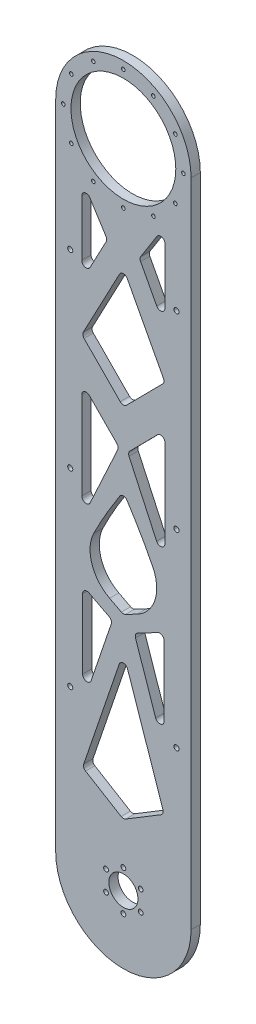
SolidWorks part; units mm, degrees
material "1060 Alloy"
ref_plane "Front Plane" through (0, 0, 0) normal (0, 0, 1) x (1, 0, 0)
ref_plane "Top Plane" through (0, 0, 0) normal (0, 1, 0) x (1, 0, 0)
ref_plane "Right Plane" through (0, 0, 0) normal (1, 0, 0) x (0, 0, -1)
sketch "Sketch2" plane through (0, 0, 0) normal (0, 0, 1) x (1, 0, 0)
  line L0 (0, 0) -> (0, 500) construction
  line L1 (-46.5, 0) -> (-46.5, 500)
  line L2 (46.5, 0) -> (46.5, 500)
  arc A0 (-46.5, 0) -> (46.5, 0) centre (0, 0) ccw
  arc A1 (46.5, 500) -> (-46.5, 500) centre (0, 500) ccw
  circle A2 centre (0, 500) radius 37.25 construction
  circle A3 centre (0, 0) radius 10
  circle A4 centre (0, 13.75) radius 1.65
  circle A5 centre (0, 0) radius 13.75 construction
  circle A6 centre (11.9078, 6.875) radius 1.65
  circle A7 centre (11.9078, -6.875) radius 1.65
  circle A8 centre (0, -13.75) radius 1.65
  circle A9 centre (-11.9078, -6.875) radius 1.65
  circle A10 centre (-11.9078, 6.875) radius 1.65
  point P3 (0, 250)
  point P27 (0, 0)
  dimension "D2" = 74.5
  dimension "D4" = 20
  dimension "D5" = 3.3
  dimension "D6" = 27.5
  dimension "D3" = 46.5
  dimension "D1" = 500
  dimension "D7" = 6
extrude "Boss-Extrude1" add sketch "Sketch2" along normal blind 6.35
sketch "Sketch4" plane through (0, 0, 6.35) normal (0, 0, 1) x (1, 0, 0)
  line L0 (0, 500) -> (0, 999.1647) construction
  line L29 (46.5, 500) -> (-46.5, 500) construction
  line L31 (28.0053, 59.376) -> (0, 42.4117)
  line L32 (0, 141.6934) -> (28.0053, 59.376)
  line L33 (-28.0053, 59.376) -> (0, 141.6934)
  line L34 (0, 42.4117) -> (-28.0053, 59.376)
  line L35 (-7.5, 156.9059) -> (-28.0053, 96.6336)
  line L36 (-28.0053, 167.5829) -> (-7.5, 156.9059)
  line L37 (-28.0053, 96.6336) -> (-28.0053, 167.5829)
  line L38 (28.0053, 167.5829) -> (7.5, 156.9059)
  line L39 (28.0053, 96.6336) -> (28.0053, 167.5829)
  line L40 (7.5, 156.9059) -> (28.0053, 96.6336)
  line L41 (0, 164.2751) -> (28.5505, 179.1412)
  line L42 (0, 164.2751) -> (-28.5505, 179.1412)
  line L43 (28.5505, 259.5868) -> (3, 314.9383)
  line L44 (28.5505, 340.7931) -> (28.5505, 259.5868)
  line L45 (3, 314.9383) -> (28.5505, 340.7931)
  line L46 (-3, 314.9383) -> (-28.5505, 340.7931)
  line L47 (-28.5505, 259.5868) -> (-3, 314.9383)
  line L48 (-28.5505, 340.7931) -> (-28.5505, 259.5868)
  line L49 (0, 423.1428) -> (-28.5505, 369.2462)
  line L50 (-28.5505, 369.2462) -> (0, 340.3557)
  line L51 (0, 340.3557) -> (28.5505, 369.2462)
  line L52 (0, 423.1428) -> (28.5505, 369.2462)
  line L53 (-28.5505, 462.0952) -> (-28.5505, 401.2902)
  line L54 (-11, 434.4215) -> (-28.5505, 462.0952)
  line L55 (-28.5505, 401.2902) -> (-11, 434.4215)
  line L56 (28.5505, 401.2902) -> (11, 434.4215)
  line L57 (28.5505, 462.0952) -> (28.5505, 401.2902)
  line L58 (11, 434.4215) -> (28.5505, 462.0952)
  arc A0 (46.5, 500) -> (-46.5, 500) centre (0, 500) ccw construction
  arc A1 (46.5, 500) -> (-46.5, 500) centre (0, 500) ccw construction
  spline S2 degree 3 poles (28.5505, 179.1412) (45.3203, 216.9857) (19.4301, 259.7903) (0, 290.0258) knots 0 0 0 0 1 1 1 1
  spline S3 degree 3 poles (-28.5505, 179.1412) (-45.3203, 216.9857) (-19.4301, 259.7903) (0, 290.0258) knots 0 0 0 0 1 1 1 1
extrude "Cut-Extrude1" cut sketch "Sketch4" against normal blind 10
fillet "Fillet3" radius 3 30 edges at (-11, 434.4215, 3.175) (-28.5505, 401.2902, 3.175) (28.5505, 401.2902, 3.175) (11, 434.4215, 3.175) (28.5505, 462.0952, 3.175) (-28.5505, 462.0952, 3.175) (0, 423.1428, 3.175) (-28.5505, 369.2462, 3.175) (28.5505, 369.2462, 3.175) (0, 340.3557, 3.175) (28.5505, 340.7931, 3.175) (-28.5505, 340.7931, 3.175) (-3, 314.9383, 3.175) (3, 314.9383, 3.175) (28.5505, 259.5868, 3.175) (-28.5505, 259.5868, 3.175) (28.5505, 179.1412, 3.175) (0, 290.0258, 3.175) (-28.5505, 179.1412, 3.175) (0, 164.2751, 3.175) (-28.0053, 96.6336, 3.175) (28.0053, 96.6336, 3.175) (7.5, 156.9059, 3.175) (-28.0053, 167.5829, 3.175) (28.0053, 167.5829, 3.175) (0, 141.6934, 3.175) (28.0053, 59.376, 3.175) (-28.0053, 59.376, 3.175) (0, 42.4117, 3.175) (-7.5, 156.9059, 3.175)
sketch "Sketch5" plane through (0, 0, 6.35) normal (0, 0, 1) x (1, 0, 0)
  line L0 (0, -46.5) -> (108.8395, -46.5) construction
  line L1 (46.5, 100) -> (-46.5, 100) construction
  line L2 (46.5, 0) -> (46.5, 500) construction
  line L3 (-46.5, 500) -> (-46.5, 0) construction
  line L4 (-46.5, 106.35) -> (46.5, 106.35) construction
  line L5 (36.5, 106.35) -> (36.5, 100) construction
  line L6 (0, 106.35) -> (0, 100) construction
  line L7 (-46.5, 256.35) -> (46.5, 256.35) construction
  line L8 (-46.5, 181.35) -> (46.5, 181.35) construction
  line L9 (-46.5, 337.7) -> (46.5, 337.7) construction
  arc A1 (-46.5, 0) -> (46.5, 0) centre (0, 0) ccw construction
  circle A2 centre (36.5, 103.175) radius 1.75
  circle A3 centre (-36.5, 103.175) radius 1.75
  circle A4 centre (36.5, 259.525) radius 1.75
  circle A5 centre (-36.5, 259.525) radius 1.75
  circle A6 centre (36.5, 415.875) radius 1.75
  circle A7 centre (-36.5, 415.875) radius 1.75
  point P18 (36.5, 103.175)
  dimension "D2" = 3.5
  dimension "D1" = 146.5
  dimension "D3" = 10
  dimension "D4" = 6.35
  dimension "D5" = 150
  dimension "D6" = 81.35
  dimension "D7" = 81.35
extrude "Cut-Extrude2" cut sketch "Sketch5" against normal through all
sketch "Sketch6" plane through (0, 0, 6.35) normal (0, 0, 1) x (1, 0, 0)
  circle A0 centre (0, 500) radius 26.5
  arc A1 (46.5, 500) -> (-46.5, 500) centre (0, 500) ccw construction
  arc A2 (46.5, 500) -> (-46.5, 500) centre (0, 500) ccw construction
  dimension "D1" = 20
extrude "Cut-Extrude3" cut sketch "Sketch6" against normal blind 10
sketch "Sketch7" plane through (0, 0, 6.35) normal (0, 0, 1) x (1, 0, 0)
  line L1 (40.0163, 523.6842) -> (44.1104, 529.9682) construction
  line L2 (23.6842, 540.0163) -> (29.9682, 544.1104) construction
  line L3 (44.1104, 529.9682) -> (29.9682, 544.1104)
  line L4 (0, 500) -> (37.0393, 537.0393) construction
  line L5 (0, 500) -> (0, 546.5) construction
  arc A0 (46.5, 500) -> (-46.5, 500) centre (0, 500) ccw construction
  arc A1 (29.9682, 544.1104) -> (16.4747, 543.4837) centre (22.4977, 559.381) cw
  arc A2 (44.1104, 529.9682) -> (43.4837, 516.4747) centre (59.381, 522.4977) ccw
  arc A3 (16.4747, 543.4837) -> (43.4837, 516.4747) centre (0, 500) cw
  dimension "D3" = 17
  dimension "D5" = 17
  dimension "D1" = 20
  dimension "D2" = 7.5
  dimension "D4" = 8
  dimension "D6" = 8
  dimension "D7" = 45
extrude "Boss-Extrude2" add sketch "Sketch7" against normal up to surface (6.35 mm away) up to face at (26.5, 500, 0)
sketch "Sketch8" plane through (287.0393, 287.0393, 0) normal (0.7071, 0.7071, 0) x (0, 0, -1)
  line L0 (0, 363.5534) -> (-6.35, 363.5534) construction
  line L1 (0, 343.5534) -> (-6.35, 343.5534) construction
  line L2 (-6.35, 343.5534) -> (-6.35, 363.5534) construction
  point P0 (-3.175, 359.5534)
  point P1 (-3.175, 347.5534)
  dimension "D1" = 4
  dimension "D2" = 4
  dimension "D3" = 3.175
hole_wizard "Tap Drill for M3x0.5 Tap1" positions "Sketch8" profile "Sketch9" hole size "M3x0.5" standard "ANSI Metric"
sketch "Sketch9" plane through (32.7967, 541.282, 3.175) normal (0, 0, 1) x (-0.7071, 0.7071, 0)
  line L0 (0, 0) -> (0, 5.7511)
  line L1 (0, 5.7511) -> (1.25, 5)
  line L2 (1.25, 5) -> (1.25, 0)
  line L5 (1.25, 0) -> (0, 0)
  line L10 (0, 5.7511) -> (-1.25, 5) construction
  line L11 (0, -6.35) -> (0, 107.95) construction
  dimension "Hole Dia." = 2.5
  dimension "Hole Depth" = 5
  dimension "Drill Angle" = 118
pattern_circular "CirPattern2" count 2 every 90 about axis through (0, 500, 0) along (0, 0, 1) of "Boss-Extrude2", "Tap Drill for M3x0.5 Tap1"
sketch "Sketch10" plane through (0, 0, 6.35) normal (0, 0, 1) x (1, 0, 0)
  line L0 (-43.4837, 516.4747) -> (-63.4837, 516.4747)
  line L1 (43.4837, 516.4747) -> (63.4837, 516.4747)
  arc A0 (43.4837, 516.4747) -> (-43.4837, 516.4747) centre (0, 500) ccw
  arc A1 (46.5, 500) -> (43.4837, 516.4747) centre (0, 500) ccw construction
  arc A2 (-63.4837, 516.4747) -> (63.4837, 516.4747) centre (0, 500) cw
  dimension "D1" = 19.0866
  dimension "D2" = 20
extrude "Cut-Extrude4" cut sketch "Sketch10" against normal through all
sketch "Sketch11" plane through (0, 0, 6.35) normal (0, 0, 1) x (1, 0, 0)
  circle A0 centre (0, 500) radius 36
  circle A1 centre (0, 500) radius 26.5 construction
  dimension "D1" = 72
extrude "Cut-Extrude5" cut sketch "Sketch11" against normal through all
sketch "Sketch12" plane through (0, 0, 6.35) normal (0, 0, 1) x (1, 0, 0)
  line L0 (0, 536) -> (0, 546.5) construction
  circle A0 centre (0, 500) radius 41.25 construction
  circle A1 centre (0, 500) radius 36 construction
  arc A2 (46.5, 500) -> (-46.5, 500) centre (0, 500) ccw construction
  circle A3 centre (0, 541.25) radius 1.25
  circle A4 centre (20.625, 535.7235) radius 1.25
  circle A5 centre (35.7235, 520.625) radius 1.25
  circle A6 centre (41.25, 500) radius 1.25
  circle A7 centre (35.7235, 479.375) radius 1.25
  circle A8 centre (20.625, 464.2765) radius 1.25
  circle A9 centre (0, 458.75) radius 1.25
  circle A10 centre (-20.625, 464.2765) radius 1.25
  circle A11 centre (-35.7235, 479.375) radius 1.25
  circle A12 centre (-41.25, 500) radius 1.25
  circle A13 centre (-35.7235, 520.625) radius 1.25
  circle A14 centre (-20.625, 535.7235) radius 1.25
  point P9 (0, 541.25)
  point P36 (0, 500)
  dimension "D1" = 2.5
  dimension "D2" = 12
extrude "Cut-Extrude6" cut sketch "Sketch12" against normal through all both and the other way through all
sketch "Sketch13" plane through (0, 0, 0) normal (0, 0, -1) x (-1, 0, 0)
  line L0 (28.984, 180.1429) -> (28.984, 234.0954) construction
  line L1 (-28.984, 180.1429) -> (-28.984, 234.0954) construction
  line L2 (46.5, 234.0954) -> (-46.5, 234.0954)
  line L3 (46.5, 500) -> (46.5, 0) construction
  line L4 (-46.5, 0) -> (-46.5, 500) construction
  line L5 (46.5, 180.1429) -> (-46.5, 180.1429)
  line L6 (-46.5, 234.0954) -> (-46.5, 180.1429)
  line L7 (46.5, 234.0954) -> (46.5, 180.1429)
  spline S0 degree 3 poles (2.5314, 286.068) (21.3968, 256.4039) (44.1773, 216.1126) (28.984, 180.1429) knots 0.042883 0.042883 0.042883 0.042883 0.991187 0.991187 0.991187 0.991187 construction
  spline S1 degree 3 poles (-28.984, 180.1429) (-44.1773, 216.1126) (-21.3968, 256.4039) (-2.5314, 286.068) knots 0.008813 0.008813 0.008813 0.008813 0.957117 0.957117 0.957117 0.957117 construction
extrude "Cut-Extrude7" cut sketch "Sketch13" against normal through all
move or copy body "Body-Move/Copy1" bodies to move or copy 111 copy no translate (0, -52.7177, 0) parameters "D1"=0, "D2"=52.7177, "D3"=0
sketch "Sketch14" plane through (0, 180.1429, 0) normal (0, 1, 0) x (1, 0, 0)
  line L0 (-28.984, 0) -> (-46.5, 0) construction
  line L1 (-46.5, 0) -> (-46.5, -6.35) construction
  line L2 (-46.5, -6.35) -> (-28.984, -6.35) construction
  line L3 (-28.984, -6.35) -> (-28.984, 0) construction
  line L4 (28.984, -6.35) -> (46.5, -6.35) construction
  line L5 (46.5, -6.35) -> (46.5, 0) construction
  line L6 (46.5, 0) -> (28.984, 0) construction
  line L7 (28.984, 0) -> (28.984, -6.35) construction
  line L8 (-28.984, 0) -> (-46.5, 0)
  line L9 (-46.5, 0) -> (-46.5, -6.35)
  line L10 (-46.5, -6.35) -> (-28.984, -6.35)
  line L11 (-28.984, -6.35) -> (-28.984, 0)
  line L12 (28.984, -6.35) -> (46.5, -6.35)
  line L13 (46.5, -6.35) -> (46.5, 0)
  line L14 (46.5, 0) -> (28.984, 0)
  line L15 (28.984, 0) -> (28.984, -6.35)
extrude "Boss-Extrude3" add sketch "Sketch14" along normal up to surface (1.2348 mm away) up to face at (37.742, 181.3777, 3.175)
sketch "Sketch15" plane through (0, 0, 0) normal (0, 0, -1) x (-1, 0, 0)
  line L0 (-1.3855, 164.9966) -> (-27.606, 178.6494) construction
  line L1 (28.984, 181.3777) -> (28.984, 180.1429)
  line L2 (-28.984, 181.3777) -> (-28.984, 180.1429) construction
  line L3 (-9.4381, 169.1895) -> (-27.606, 178.6494)
  line L4 (-28.984, 181.3777) -> (-28.984, 180.1429)
  line L5 (0, 493.7823) -> (0, -46.5) construction
  line L6 (9.4381, 169.1895) -> (27.606, 178.6494)
  arc A0 (-20.3344, 202.3794) -> (-9.4381, 169.1895) centre (2.1078, 191.3636) ccw
  arc A1 (-28.984, 180.1429) -> (-27.606, 178.6494) centre (-26.2204, 181.3103) ccw construction
  arc A2 (-28.984, 180.1429) -> (-27.606, 178.6494) centre (-26.2204, 181.3103) ccw
  arc A3 (46.5, 447.2823) -> (-46.5, 447.2823) centre (0, 447.2823) ccw construction
  arc A4 (-46.5, 0) -> (46.5, 0) centre (0, 0) ccw construction
  arc A5 (28.984, 180.1429) -> (27.606, 178.6494) centre (26.2204, 181.3103) cw
  arc A6 (20.3344, 202.3794) -> (9.4381, 169.1895) centre (-2.1078, 191.3636) cw
  spline S0 degree 3 poles (1953.7087, 263.1445) (-2215.7642, -533.3919) (2154.4506, 1213.369) (-1849.5555, -532.5784) knots -2.670349 -2.670349 -2.670349 -2.670349 4.338748 4.338748 4.338748 4.338748 only from (-28.984, 181.3777) to (-2.5314, 233.3503) construction
  spline S1 degree 3 poles (28.984, 181.3777) (26.6659, 188.5284) (23.6788, 195.566) (20.3344, 202.3794) knots 0.47109 0.47109 0.47109 0.47109 0.656208 0.656208 0.656208 0.656208
  spline S2 degree 3 poles (-28.984, 181.3777) (-26.6659, 188.5284) (-23.6788, 195.566) (-20.3344, 202.3794) knots 0.47109 0.47109 0.47109 0.47109 0.656208 0.656208 0.656208 0.656208
  dimension "D1" = 25
  dimension "D2" = 540.2823
extrude "Boss-Extrude4" add sketch "Sketch15" against normal up to surface (6.35 mm away) up to face at (2.6453, 187.7844, 6.35)
sketch "Sketch16" plane through (0, 0, 0) normal (0, 0, -1) x (-1, 0, 0)
  line L0 (36.5, 103.175) -> (36.5, 363.1573) construction
  line L1 (-36.5, 103.175) -> (-36.5, 363.1573) construction
  circle A0 centre (-36.5, 363.1573) radius 1.75 construction
  circle A1 centre (36.5, 363.1573) radius 1.75 construction
  circle A2 centre (-36.5, 103.175) radius 1.75 construction
  circle A3 centre (36.5, 103.175) radius 1.75 construction
  circle A4 centre (-36.5, 363.1573) radius 1.75 construction
  circle A5 centre (36.5, 363.1573) radius 1.75 construction
  circle A6 centre (-36.5, 103.175) radius 1.75 construction
  circle A7 centre (36.5, 103.175) radius 1.75 construction
  circle A8 centre (36.5, 233.1662) radius 1.75
  circle A9 centre (-36.5, 233.1662) radius 1.75
  point P16 (36.5, 233.1662)
  point P17 (36.5, 281.5314)
  point P18 (36.5, 233.1662)
  point P19 (0, 0)
extrude "Cut-Extrude8" cut sketch "Sketch16" against normal through all
sketch "Sketch17" plane through (0, 0, 0) normal (0, 0, -1) x (-1, 0, 0)
  circle A0 centre (36.5, 206.8073) radius 1.75 construction
  circle A1 centre (-36.5, 206.8073) radius 1.75 construction
  circle A2 centre (36.5, 206.8073) radius 1.75
  circle A3 centre (-36.5, 206.8073) radius 1.75
extrude "Boss-Extrude5" add sketch "Sketch17" against normal up to surface (6.35 mm away) up to face at (-34.75, 233.1662, 6.35)
equation "\"L1L\"=500"
equation "\"L1Thick\"=6.35"
equation "\"D1@Sketch2\"=\"L1L\""
equation "\"Harm-Drive-Outer\"=74.5"
equation "\"D2@Sketch2\"=\"Harm-Drive-Outer\""
equation "\"D1@Boss-Extrude1\"=\"L1Thick\""
